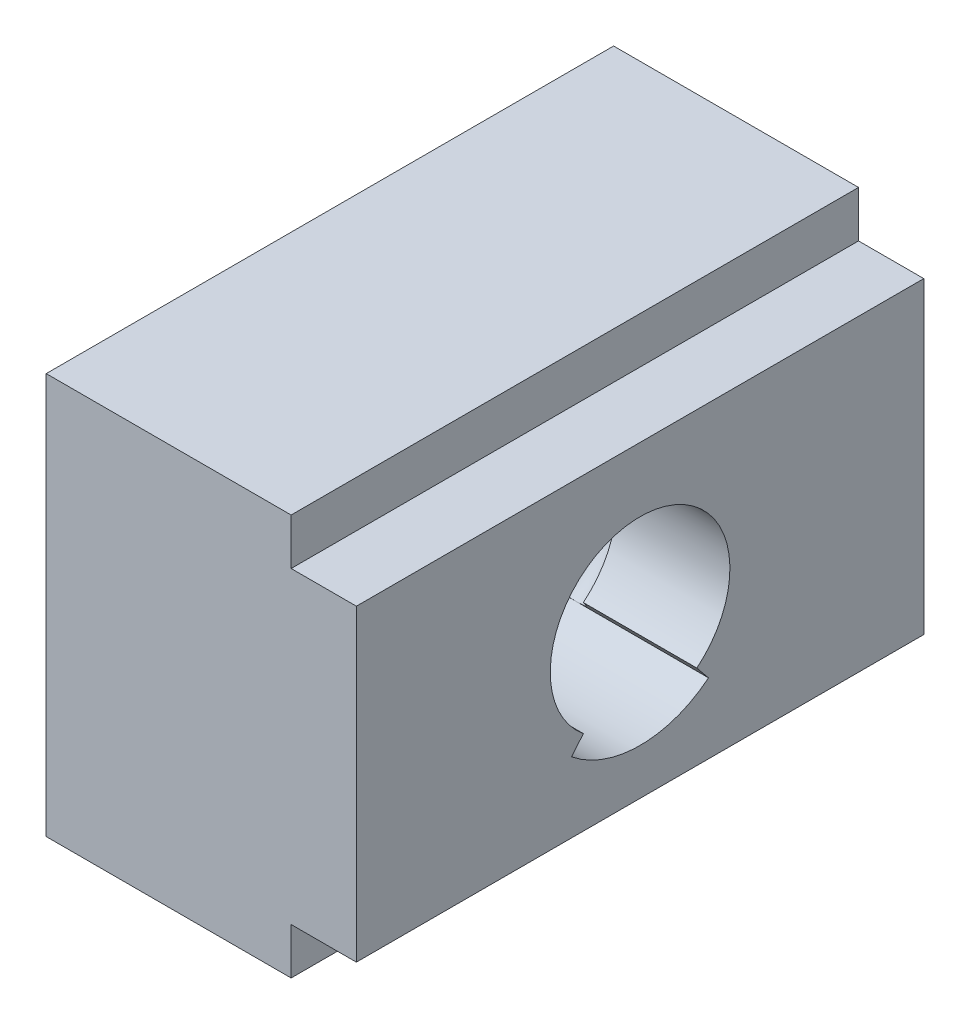
SolidWorks part; units mm, degrees
ref_plane "Front Plane" through (0, 0, 0) normal (0, 0, 1) x (1, 0, 0)
ref_plane "Top Plane" through (0, 0, 0) normal (0, 1, 0) x (1, 0, 0)
ref_plane "Right Plane" through (0, 0, 0) normal (1, 0, 0) x (0, 0, -1)
sketch "Sketch1" plane through (0, 0, 0) normal (0, 0, 1) x (1, 0, 0)
  line L0 (94.9387, 94.6033) -> (60.4387, 94.6033)
  line L1 (60.4387, 94.6033) -> (60.4387, 119.1033)
  line L2 (60.4387, 119.1033) -> (-69.0613, 119.1033)
  line L3 (-69.0613, 119.1033) -> (-69.0613, -92.8967)
  line L4 (-69.0613, -92.8967) -> (60.4387, -92.8967)
  line L5 (60.4387, -92.8967) -> (60.4387, -68.3967)
  line L6 (60.4387, -68.3967) -> (94.9387, -68.3967)
  line L7 (94.9387, -68.3967) -> (94.9387, 94.6033)
  point P8 (60.4387, 106.8533)
  dimension "D1" = 24.5
  dimension "D2" = 34.5
  dimension "D3" = 212
  dimension "D4" = 129.5
extrude "Boss-Extrude1" add sketch "Sketch1" along normal blind 300
sketch "Sketch2" plane through (94.9387, 0, 0) normal (1, 0, 0) x (0, 0, -1)
  line L0 (-300, 94.6033) -> (0, -68.3967) construction
  line L1 (0, 94.6033) -> (-300, -68.3967) construction
  circle A0 centre (-150, 13.1033) radius 47.5
  dimension "D1" = 95
extrude "Cut-Extrude1" cut sketch "Sketch2" against normal blind 100
ref_plane "Plane1" through (0, 0, 150) normal (0, 0, 1) x (1, 0, 0)
sketch "Sketch3" plane through (0, 0, 150) normal (0, 0, 1) x (1, 0, 0)
  circle A0 centre (24.9387, 60.3731) radius 10
  dimension "D1" = 20
ref_plane "Plane2" through (25, 0, 0) normal (1, 0, 0) x (0, 0, -1)
sketch "Sketch5" plane through (25, 0, 0) normal (1, 0, 0) x (0, 0, -1)
  line L1 (-120, -54.1006) -> (-180, -54.1006)
  arc A0 (-120, -23.724) -> (-180, -23.724) centre (-150, 13.1033) ccw
sweep "Cut-Sweep1" cut profiles "Sketch3" path "Sketch5"
sketch "Sketch7" plane through (94.9387, 0, 0) normal (1, 0, 0) x (0, 0, -1)
  line L0 (-180, -23.724) -> (-186.1704, -31.2986)
  line L5 (-120, -23.724) -> (-113.8296, -31.2986)
  circle A0 centre (-150, 13.1033) radius 47.5 construction
  arc A1 (-180, -23.724) -> (-120, -23.724) centre (-150, 13.1033) ccw
  arc A2 (-186.1704, -31.2986) -> (-113.8296, -31.2986) centre (-150, 13.1033) ccw
  point P0 (-150, -34.3967)
extrude "Cut-Extrude3" cut sketch "Sketch7" against normal up to surface (100 mm away) up to face at (-5.0613, 13.1033, 102.5)
sketch "Sketch8" plane through (0, 0, 150) normal (0, 0, 1) x (1, 0, 0)
  line L0 (-69.0613, -92.8967) -> (94.9387, 119.1033) construction
  line L1 (-69.0613, 119.1033) -> (94.9387, -92.8967) construction
  line L2 (12.9387, 13.1033) -> (-5.0613, 13.1033) construction
  line L3 (-5.0613, -23.724) -> (-5.0613, 60.6033) construction
  point P6 (12.9387, 13.1033)
  point P7 (12.9387, 13.1033)
ref_plane "Plane3" through (0, 13.1033, 0) normal (0, 1, 0) x (1, 0, 0)
sketch "Sketch9" plane through (0, 13.1033, 0) normal (0, 1, 0) x (1, 0, 0)
  line L0 (12.9387, 300) -> (-4.3113, 300) construction
  line L1 (12.9387, -150) -> (12.9387, 300) construction
  point P3 (12.9387, 300)
  dimension "D1" = 17.25
  dimension "D2" = 450
sketch "Sketch10" plane through (0, 0, 0) normal (0, 1, 0) x (1, 0, 0)
  line L0 (-69.0613, -300) -> (94.9387, 0) construction
  line L1 (94.9387, -300) -> (-69.0613, 0) construction
  point P8 (12.9387, -150)
